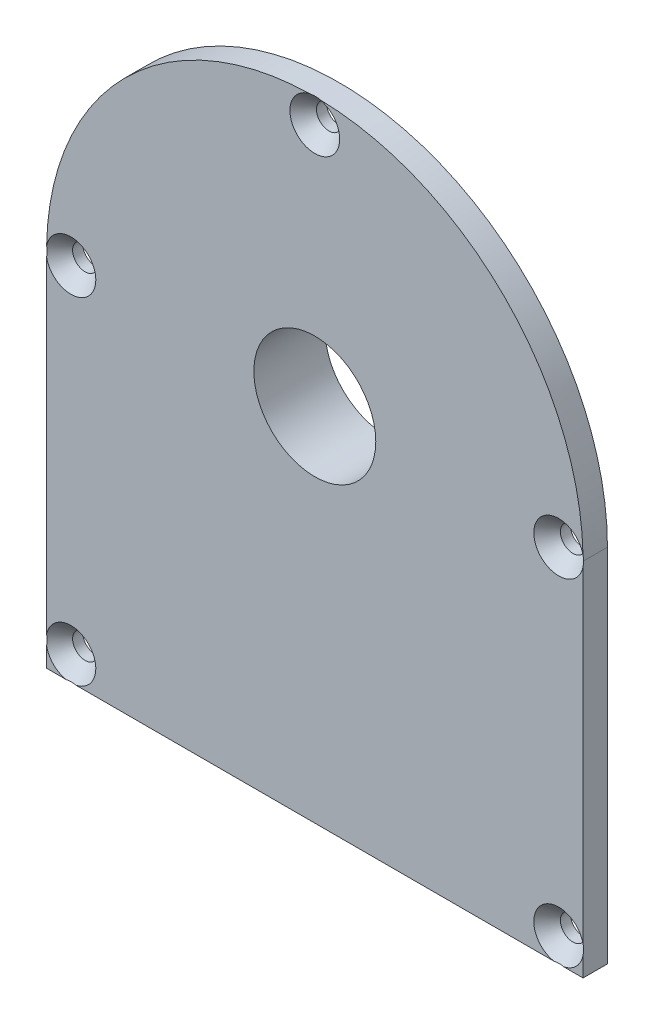
SolidWorks part; units mm, degrees
material "6061 Alloy"
ref_plane "Front Plane" through (0, 0, 0) normal (0, 0, 1) x (1, 0, 0)
ref_plane "Top Plane" through (0, 0, 0) normal (0, 1, 0) x (1, 0, 0)
ref_plane "Right Plane" through (0, 0, 0) normal (1, 0, 0) x (0, 0, -1)
sketch "Sketch1" plane through (0, 0, 0) normal (0, 0, 1) x (1, 0, 0)
  line L0 (-34.925, 5.715) -> (-34.925, -41.275) construction
  line L2 (34.925, -41.275) -> (34.925, 5.715) construction
  line L3 (-34.925, 5.715) -> (-34.925, -41.275)
  line L4 (-34.925, -41.275) -> (34.925, -41.275)
  line L5 (34.925, -41.275) -> (34.925, 5.715)
  arc A0 (34.925, 5.715) -> (-34.925, 5.715) centre (0, 5.715) ccw construction
  arc A1 (34.925, 5.715) -> (-34.925, 5.715) centre (0, 5.715) ccw
extrude "Boss-Extrude1" add sketch "Sketch1" along normal blind 3.175
sketch "Sketch2" plane through (0, 0, 3.175) normal (0, 0, 1) x (1, 0, 0)
  circle A0 centre (0, 5.715) radius 7.9375
  dimension "D1" = 15.875
extrude "Cut-Extrude1" cut sketch "Sketch2" against normal blind 3.175
hole_wizard "CSK for #4 Flat Head Socket Cap Screw1" positions "Sketch4" profile "Sketch5" countersink size "#4" standard "Ansi Inch" end condition through all
sketch "Sketch4" plane through (0, 0, 3.175) normal (0, 0, 1) x (1, 0, 0)
  point P5 (0, 37.465)
  point P8 (-31.75, 5.715)
  point P11 (31.75, 5.715)
  point P14 (31.75, -38.1)
  point P17 (-31.75, -38.1)
sketch "Sketch5" plane through (0, 37.465, 3.175) normal (1, 0, 0) x (0, -1, 0)
  line L0 (0, 0) -> (0, 3.175)
  line L1 (0, 3.175) -> (1.6319, 3.175)
  line L2 (1.6319, 3.175) -> (1.6319, 1.8481)
  line L3 (1.6319, 1.8481) -> (3.2385, 0)
  line L5 (3.2385, 0) -> (0, 0)
  line L6 (-1.632, 1.8481) -> (-3.2385, 0) construction
  line L11 (0, -6.35) -> (0, 107.95) construction
  dimension "Thru Hole Dia." = 3.2639
  dimension "Thru Hole Depth" = 3.175
  dimension "Near C'Sink Dia." = 6.477
  dimension "Near C'Sink Angle" = 82
sketch "Sketch6" plane through (0, 0, 0) normal (0, 0, -1) x (-1, 0, 0)
  circle A0 centre (0, 5.715) radius 11.1125
  circle A1 centre (0, 5.715) radius 7.9375
  circle A2 centre (0, 5.715) radius 7.9375 construction
  dimension "D1" = 22.225
extrude "Boss-Extrude2" add sketch "Sketch6" along normal offset from surface (6.096 mm away) 9.271 up to face at (0, -3.8834, 3.175)
sketch "Sketch7" plane through (0, 0, 0) normal (0, 0, -1) x (-1, 0, 0)
  line L0 (34.925, 5.715) -> (34.925, -41.275) construction
  circle A0 centre (15.875, -25.3935) radius 6.35
  circle A1 centre (15.875, -25.3935) radius 8.7313
  circle A2 centre (0, 5.715) radius 7.9375 construction
  dimension "D1" = 12.7
  dimension "D2" = 17.4625
  dimension "D3" = 34.925
  dimension "D4" = 19.05
extrude "Boss-Extrude3" add sketch "Sketch7" along normal blind 3.556
sketch "Sketch8" plane through (0, 0, 0) normal (0, 0, -1) x (-1, 0, 0)
  circle A0 centre (15.875, -25.3935) radius 6.35
  circle A1 centre (15.875, -25.3935) radius 6.35 construction
extrude "Cut-Extrude2" cut sketch "Sketch8" against normal blind 2.032
fillet "Fillet1" radius 3.175 2 edges at (11.1125, 5.715, 0) (-7.1437, -25.3935, 0)
